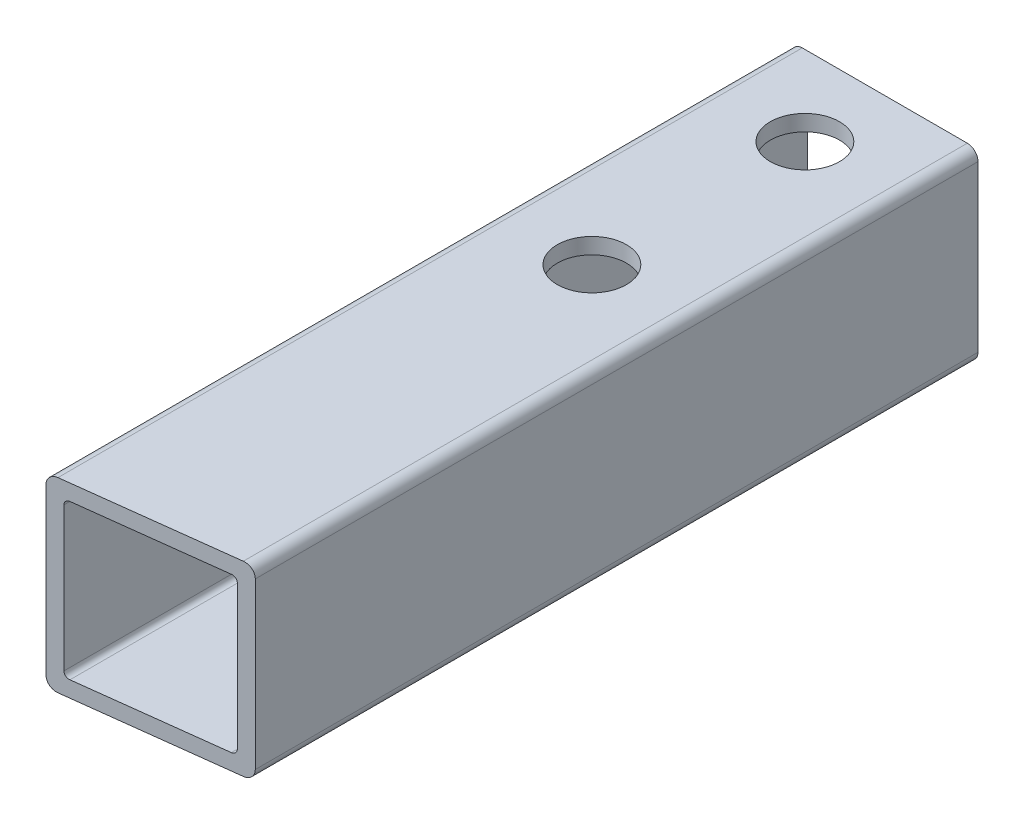
SolidWorks part; units mm, degrees
material "1.0553 (S355J0)"
ref_plane "Płaszczyzna przednia" through (0, 0, 0) normal (0, 0, 1) x (1, 0, 0)
ref_plane "Płaszczyzna górna" through (0, 0, 0) normal (0, 1, 0) x (1, 0, 0)
ref_plane "Płaszczyzna prawa" through (0, 0, 0) normal (1, 0, 0) x (0, 0, -1)
sketch "Szkic1" plane through (0, 0, 0) normal (0, 0, 1) x (1, 0, 0)
  line L1 (-15.5, 0) -> (15.5, 0)
  line L2 (-17.5, 2) -> (-17.5, 33)
  line L3 (-15.5, 35) -> (15.5, 35)
  line L4 (17.5, 2) -> (17.5, 33)
  line L5 (-13.5, 3) -> (13.5, 3)
  line L6 (-14.5, 4) -> (-14.5, 31)
  line L7 (-13.5, 32) -> (13.5, 32)
  line L8 (14.5, 4) -> (14.5, 31)
  arc A0 (-17.5, 2) -> (-15.5, 0) centre (-15.5, 2) ccw
  arc A1 (15.5, 0) -> (17.5, 2) centre (15.5, 2) ccw
  arc A2 (17.5, 33) -> (15.5, 35) centre (15.5, 33) ccw
  arc A3 (-15.5, 35) -> (-17.5, 33) centre (-15.5, 33) ccw
  arc A4 (-14.5, 4) -> (-13.5, 3) centre (-13.5, 4) ccw
  arc A5 (13.5, 3) -> (14.5, 4) centre (13.5, 4) ccw
  arc A6 (14.5, 31) -> (13.5, 32) centre (13.5, 31) ccw
  arc A7 (-13.5, 32) -> (-14.5, 31) centre (-13.5, 31) ccw
  point P7 (0, 0)
  dimension "D3" = 2
  dimension "D8" = 1
  dimension "D1" = 35
  dimension "D2" = 35
  dimension "D4" = 3
  dimension "D5" = 3
  dimension "D6" = 3
  dimension "D7" = 3
extrude "Dodanie-wyciągnięcie1" add sketch "Szkic1" along normal blind 140
sketch "Szkic2" plane through (0, 35, 0) normal (0, 1, 0) x (1, 0, 0)
  line L0 (-17.5, -140) -> (23.8917, -134.9177)
  line L1 (-17.5, -140) -> (23.8917, -140)
  line L2 (23.8917, -140) -> (23.8917, -134.9177)
  line L3 (0, 0) -> (0, -145.9665) construction
  line L4 (15.5, 0) -> (-15.5, 0) construction
  circle A0 centre (0, -15) radius 6.5
  circle A1 centre (0, -55) radius 6.5
  dimension "D2" = 13
  dimension "D1" = 7
  dimension "D3" = 40
  dimension "D4" = 15
extrude "Wytnij-wyciągnięcie1" cut sketch "Szkic2" against normal blind 140
